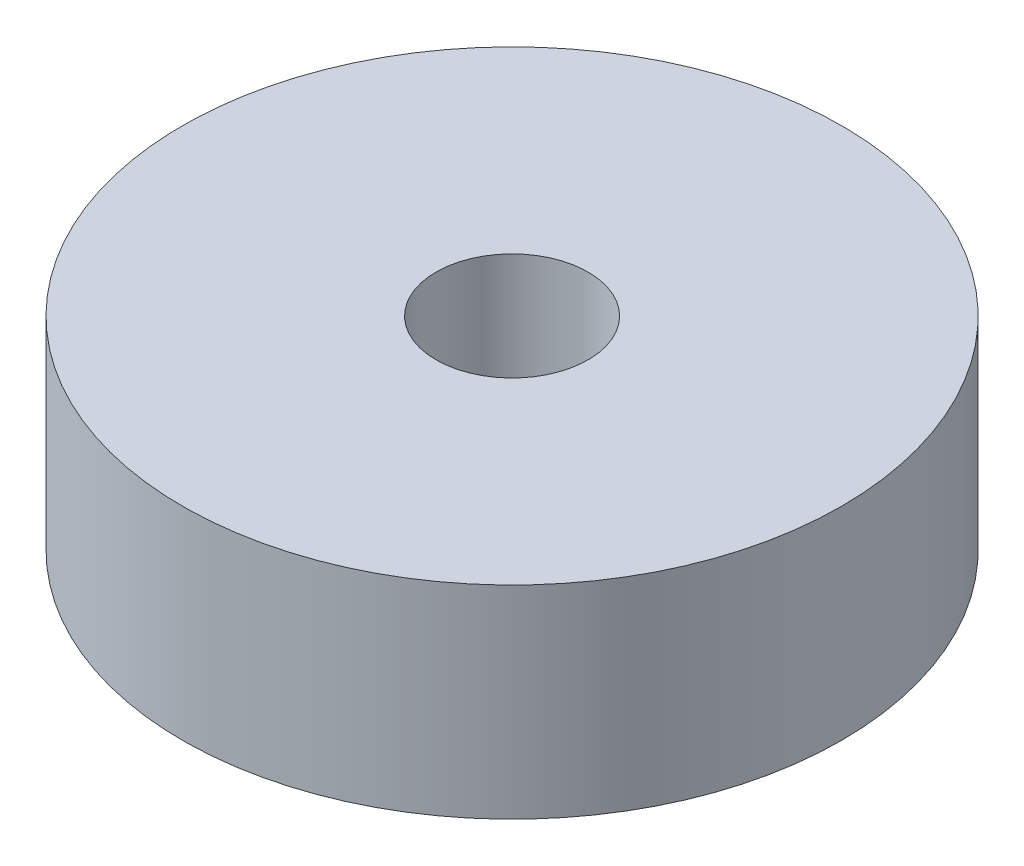
SolidWorks part; units mm, degrees
ref_plane "Front Plane" through (0, 0, 0) normal (0, 0, 1) x (1, 0, 0)
ref_plane "Top Plane" through (0, 0, 0) normal (0, 1, 0) x (1, 0, 0)
ref_plane "Right Plane" through (0, 0, 0) normal (1, 0, 0) x (0, 0, -1)
sketch "Sketch1" plane through (0, 0, 0) normal (0, 1, 0) x (1, 0, 0)
  circle A1 centre (0, 0) radius 1.5
  dimension "D2" = 3
extrude "Extrude-Thin1" add sketch "Sketch1" along normal blind 4 thin contours A1
